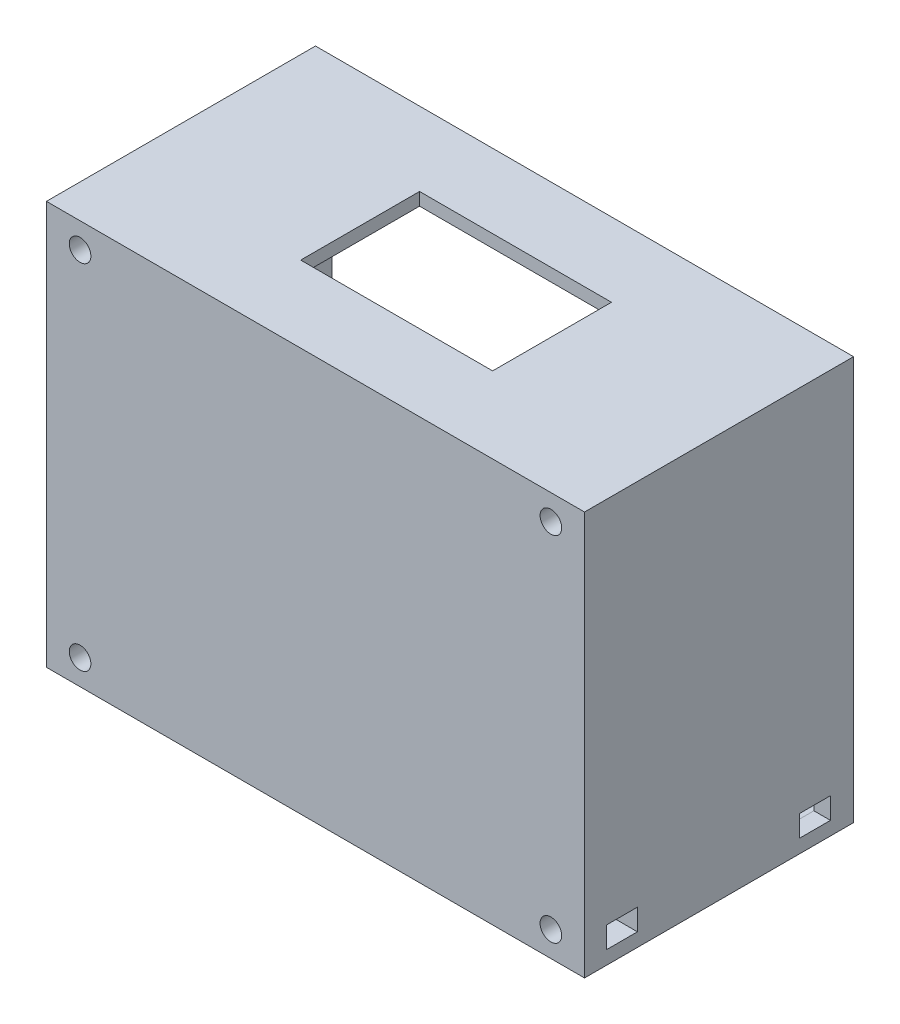
SolidWorks part; units mm, degrees
ref_plane "Plano frontal" through (0, 0, 0) normal (0, 0, 1) x (1, 0, 0)
ref_plane "Plano superior" through (0, 0, 0) normal (0, 1, 0) x (1, 0, 0)
ref_plane "Plano direito" through (0, 0, 0) normal (1, 0, 0) x (0, 0, -1)
sketch "Esboço1" plane through (0, 0, 0) normal (0, 0, 1) x (1, 0, 0)
  line L0 (-100, 0) -> (100, 0) construction
  line L1 (100, -75) -> (-100, -75)
  line L2 (100, -75) -> (100, 75)
  line L3 (100, 75) -> (-100, 75)
  line L4 (-100, -75) -> (-100, 75)
  line L5 (100, -75) -> (-100, 75) construction
  line L6 (100, 75) -> (-100, -75) construction
  line L7 (0, -75) -> (0, 75) construction
  circle A1 centre (-87.5007, 65.6255) radius 4.0159
  circle A2 centre (-87.5007, -65.6255) radius 4.0159
  circle A3 centre (87.5007, 65.6255) radius 4.0159
  circle A4 centre (87.5007, -65.6255) radius 4.0159
  point P0 (0, 0)
  dimension "D1" = 150
  dimension "D2" = 200
extrude "Ressalto-extrusão1" add sketch "Esboço1" along normal blind 100
sketch "Esboço2" plane through (0, 0, 0) normal (0, 0, 1) x (1, 0, 0)
  line L1 (93.835, -70.2652) -> (-93.835, -70.2652)
  line L2 (93.835, -70.2652) -> (93.835, 70.2652)
  line L3 (93.835, 70.2652) -> (-93.835, 70.2652)
  line L4 (-93.835, -70.2652) -> (-93.835, 70.2652)
  line L5 (93.835, -70.2652) -> (-93.835, 70.2652) construction
  line L6 (93.835, 70.2652) -> (-93.835, -70.2652) construction
  point P0 (0, 0)
extrude "Corte-extrusão2" cut sketch "Esboço2" along normal blind 80
sketch "Esboço3" plane through (0, 0, 0) normal (1, 0, 0) x (0, 0, -1)
  line L1 (-33.685, -61.3905) -> (-7.9575, -61.3905)
  line L2 (-33.685, -61.3905) -> (-33.685, -70.3847)
  line L3 (-33.685, -70.3847) -> (-7.9575, -70.3847)
  line L4 (-7.9575, -61.3905) -> (-7.9575, -70.3847)
extrude "Corte-extrusão3" cut sketch "Esboço3" against normal blind 103
sketch "Esboço4" plane through (0, 0, 0) normal (1, 0, 0) x (0, 0, -1)
  line L1 (-91.8334, -62.018) -> (-80.3292, -62.018)
  line L2 (-91.8334, -62.018) -> (-91.8334, -69.9663)
  line L3 (-91.8334, -69.9663) -> (-80.3292, -69.9663)
  line L4 (-80.3292, -62.018) -> (-80.3292, -69.9663)
  line L5 (-20.0891, -62.018) -> (-8.585, -62.018)
  line L6 (-20.0891, -62.018) -> (-20.0891, -69.9663)
  line L7 (-20.0891, -69.9663) -> (-8.585, -69.9663)
  line L8 (-8.585, -62.018) -> (-8.585, -69.9663)
extrude "Corte-extrusão4" cut sketch "Esboço4" along normal blind 114
sketch "Esboço5" plane through (0, 75, 0) normal (0, 1, 0) x (1, 0, 0)
  line L1 (-33.8343, -27.4797) -> (37.4979, -27.4797)
  line L2 (-33.8343, -27.4797) -> (-33.8343, -71.6583)
  line L3 (-33.8343, -71.6583) -> (37.4979, -71.6583)
  line L4 (37.4979, -27.4797) -> (37.4979, -71.6583)
extrude "Corte-extrusão5" cut sketch "Esboço5" against normal blind 114
